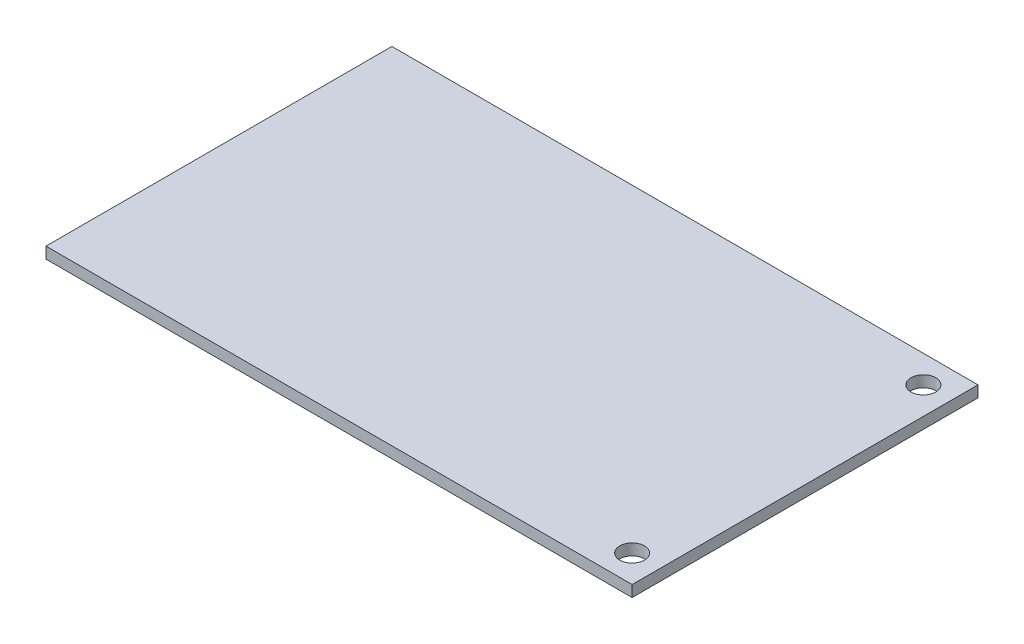
SolidWorks part; units mm, degrees
ref_plane "Front Plane" through (0, 0, 0) normal (0, 0, 1) x (1, 0, 0)
ref_plane "Top Plane" through (0, 0, 0) normal (0, 1, 0) x (1, 0, 0)
ref_plane "Right Plane" through (0, 0, 0) normal (1, 0, 0) x (0, 0, -1)
sketch "Sketch1" plane through (0, 0, 0) normal (0, 1, 0) x (1, 0, 0)
  line L0 (0, 0) -> (67.5792, 0) construction
  line L1 (40.894, -24.13) -> (-40.894, -24.13)
  line L2 (40.894, -24.13) -> (40.894, 24.13)
  line L3 (40.894, 24.13) -> (-40.894, 24.13)
  line L4 (-40.894, -24.13) -> (-40.894, 24.13)
  line L5 (40.894, -24.13) -> (-40.894, 24.13) construction
  line L6 (40.894, 24.13) -> (-40.894, -24.13) construction
  circle A0 centre (37.084, 20.32) radius 1.7272
  circle A1 centre (37.084, -20.32) radius 1.7272
  point P0 (0, 0)
  dimension "D3" = 3.81
  dimension "D4" = 3.4544
  dimension "D5" = 3.81
  dimension "D1" = 48.26
  dimension "D2" = 81.788
extrude "Boss-Extrude1" add sketch "Sketch1" along normal blind 1.5748
